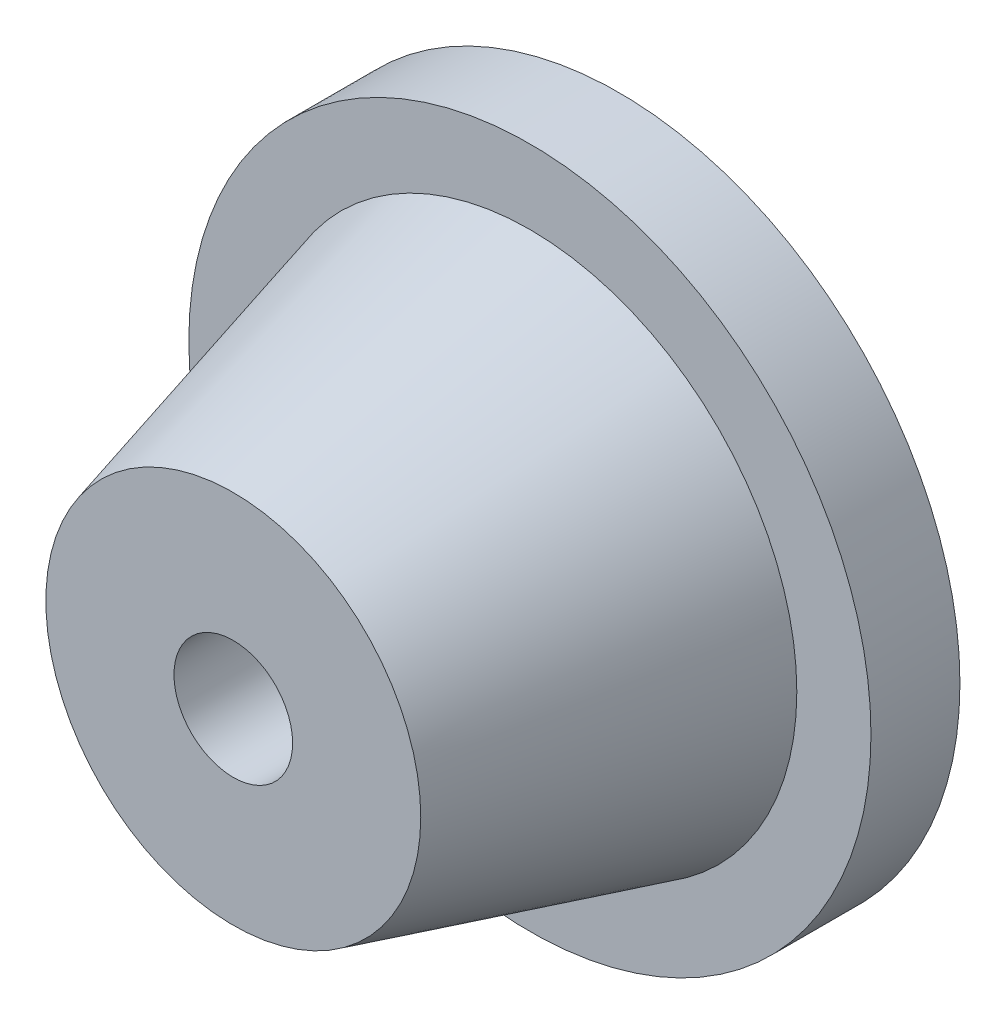
SolidWorks part; units mm, degrees
ref_plane "Front Plane" through (0, 0, 0) normal (0, 0, 1) x (1, 0, 0)
ref_plane "Top Plane" through (0, 0, 0) normal (0, 1, 0) x (1, 0, 0)
ref_plane "Right Plane" through (0, 0, 0) normal (1, 0, 0) x (0, 0, -1)
sketch "Sketch1" plane through (0, 0, 0) normal (0, 0, 1) x (1, 0, 0)
  circle A0 centre (0, 0) radius 11.5
  dimension "D1" = 23
extrude "Boss-Extrude1" add sketch "Sketch1" along normal blind 3
sketch "Sketch2" plane through (0, 0, 3) normal (0, 0, 1) x (1, 0, 0)
  circle A0 centre (0, 0) radius 9
  dimension "D1" = 18
extrude "Boss-Extrude2" add sketch "Sketch2" along normal blind 10 draft 15
sketch "Sketch3" plane through (0, 0, 13) normal (0, 0, 1) x (1, 0, 0)
  circle A0 centre (0, 0) radius 2
  dimension "D1" = 4
extrude "Cut-Extrude1" cut sketch "Sketch3" against normal through all
